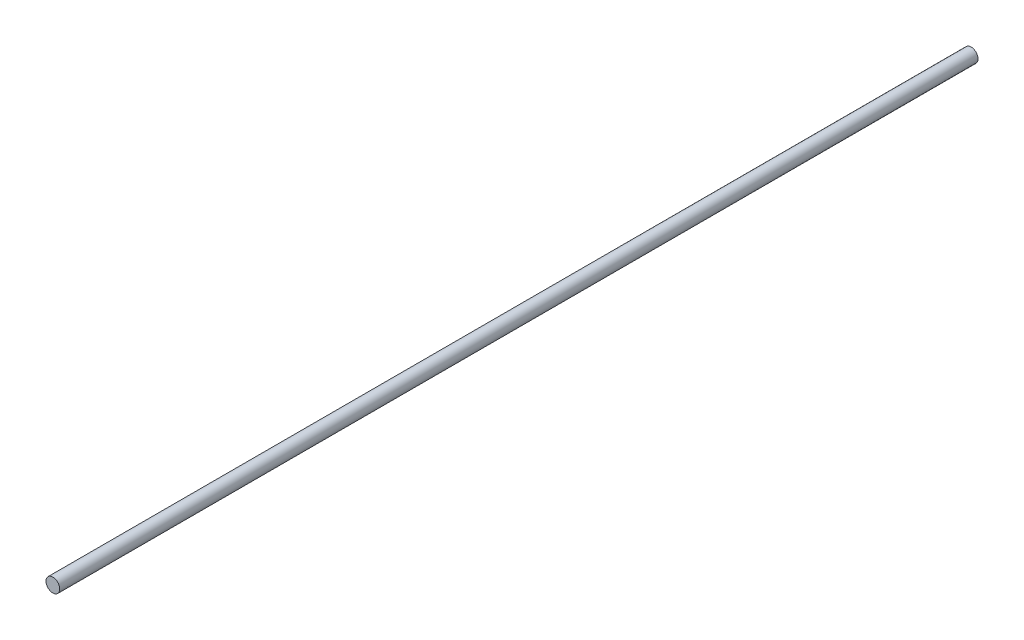
SolidWorks part; units mm, degrees
ref_plane "Front Plane" through (0, 0, 0) normal (0, 0, 1) x (1, 0, 0)
ref_plane "Top Plane" through (0, 0, 0) normal (0, 1, 0) x (1, 0, 0)
ref_plane "Right Plane" through (0, 0, 0) normal (1, 0, 0) x (0, 0, -1)
sketch "Sketch1" plane through (0, 0, 0) normal (0, 0, 1) x (1, 0, 0)
  circle A0 centre (0, 0) radius 3
extrude "Boss-Extrude1" add sketch "Sketch1" along normal blind 400
